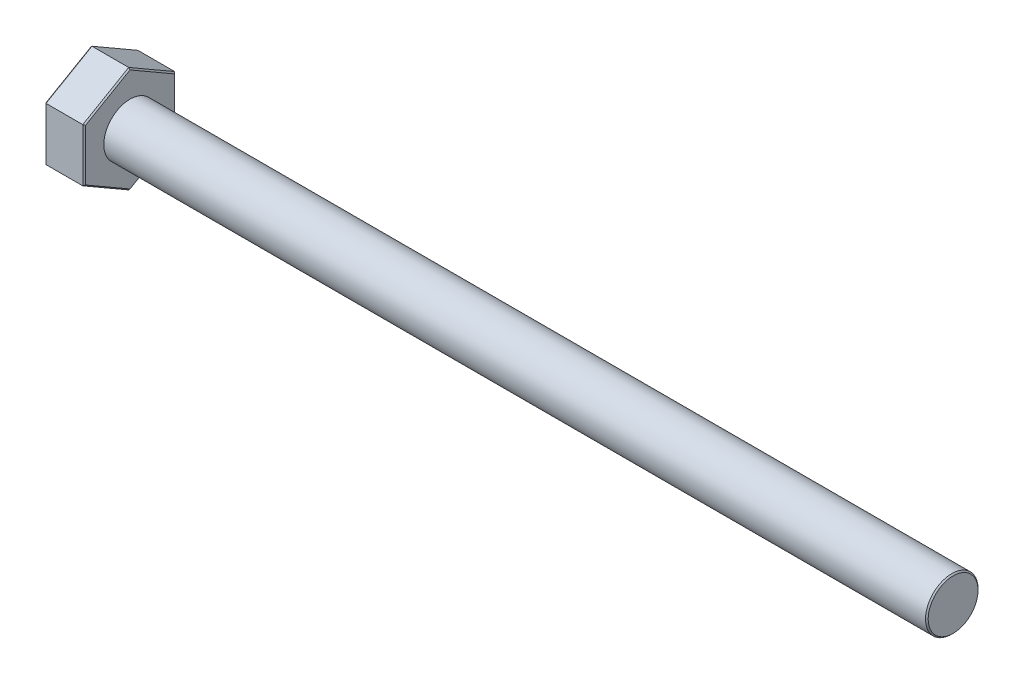
SolidWorks part; units mm, degrees
material "CRCA"
ref_plane "Front Plane" through (0, 0, 0) normal (0, 0, 1) x (1, 0, 0)
ref_plane "Top Plane" through (0, 0, 0) normal (0, 1, 0) x (1, 0, 0)
ref_plane "Right Plane" through (0, 0, 0) normal (1, 0, 0) x (0, 0, -1)
sketch "Sketch1" plane through (0, 0, 0) normal (0, 0, 1) x (1, 0, 0)
  line L0 (-15.5547, 0) -> (34.7607, 0) construction
  line L1 (0, 0) -> (0, 2)
  line L2 (0, 2) -> (62.7, 2)
  line L3 (62.7, 2) -> (62.7, 0)
  line L4 (62.7, 0) -> (0, 0)
  dimension "D1" = 4
  dimension "D2" = 62.7
revolve "Revolve1" add sketch "Sketch1" angle 360 about L0
cosmetic thread "Cosmetic Thread1" [suppressed] parameters "D1"=14, "D2"=3.22
sketch "Sketch2" plane through (0, 0, 0) normal (-1, 0, 0) x (0, 0, 1)
  line L1 (0, 4.0415) -> (-3.5, 2.0207)
  line L2 (-3.5, 2.0207) -> (-3.5, -2.0207)
  line L3 (-3.5, -2.0207) -> (0, -4.0415)
  line L4 (0, -4.0415) -> (3.5, -2.0207)
  line L5 (3.5, -2.0207) -> (3.5, 2.0207)
  line L6 (3.5, 2.0207) -> (0, 4.0415)
  circle A0 centre (0, 0) radius 3.5 construction
  dimension "D1" = 7
extrude "Boss-Extrude1" add sketch "Sketch2" along normal blind 3
chamfer "Chamfer1" distance 0.1 angle 45 12 edges at (-3, 0, 3.5) (-3, -3.0311, 1.75) (-3, -3.0311, -1.75) (-3, 0, -3.5) (-3, 3.0311, -1.75) (-3, 3.0311, 1.75) (0, -3.0311, -1.75) (0, -3.0311, 1.75) (0, 0, 3.5) (0, 3.0311, 1.75) (0, 3.0311, -1.75) (0, 0, -3.5)
chamfer "Chamfer2" distance 0.1 angle 45 1 edges at (62.7, 0, 2)
